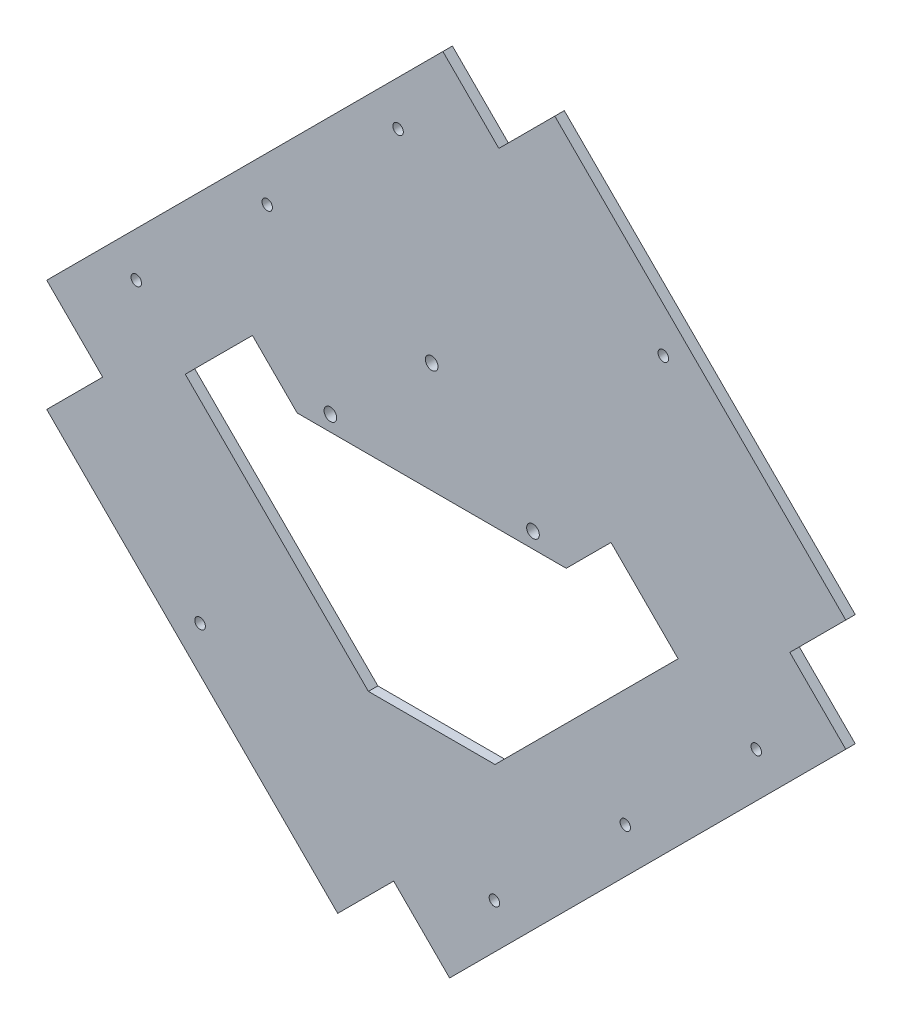
SolidWorks part; units mm, degrees
material "Thornel Mat VMA"
ref_plane "前视基准面" through (0, 0, 0) normal (0, 0, 1) x (1, 0, 0)
ref_plane "上视基准面" through (0, 0, 0) normal (0, 1, 0) x (1, 0, 0)
ref_plane "右视基准面" through (0, 0, 0) normal (1, 0, 0) x (0, 0, -1)
sketch "草图1" plane through (0, 0, 0) normal (0, 0, 1) x (1, 0, 0)
  line L0 (-20, 0) -> (20, 0)
  line L1 (0, 211.4264) -> (0, -109.6) construction
  line L2 (20, 0) -> (77.8553, 57.8553)
  line L3 (77.8553, 57.8553) -> (56.6421, 79.0685)
  line L4 (56.6421, 79.0685) -> (42.5, 64.9264)
  line L5 (42.5, 64.9264) -> (-42.5, 64.9264)
  line L6 (-42.5, 64.9264) -> (-56.6421, 79.0685)
  line L7 (-56.6421, 79.0685) -> (-77.8553, 57.8553)
  line L8 (-77.8553, 57.8553) -> (-20, 0)
  line L10 (-77.8553, 101.8264) -> (77.8553, 101.8264) construction
  line L11 (-77.8553, 101.8264) -> (-77.8553, 0) construction
  line L12 (-77.8553, 0) -> (77.8553, 0) construction
  line L13 (77.8553, 101.8264) -> (77.8553, 0) construction
  line L14 (-77.8553, 101.8264) -> (77.8553, 0) construction
  line L15 (-77.8553, 0) -> (77.8553, 101.8264) construction
  line L19 (0, 50.9132) -> (160.5132, 50.9132) construction
  line L26 (0, 50.9132) -> (-160.5132, 50.9132) construction
  line L27 (-160.5132, 50.9132) -> (0, 211.4264)
  line L28 (0, 211.4264) -> (160.5132, 50.9132)
  line L29 (160.5132, 50.9132) -> (0, -109.6)
  line L30 (0, -109.6) -> (-160.5132, 50.9132)
  circle A0 centre (-32, 69.8264) radius 2
  circle A1 centre (32, 69.8264) radius 2
  circle A2 centre (0, 99.8264) radius 2
  point P13 (0, 50.9132)
  point P18 (0, 50.9132)
  dimension "D5" = 4.9
  dimension "D6" = 4
  dimension "D7" = 34.9
  dimension "D8" = 64
  dimension "D1" = 85
  dimension "D2" = 40
  dimension "D3" = 30
  dimension "D4" = 20
  dimension "D9" = 227
extrude "凸台-拉伸1" add sketch "草图1" along normal blind 3
sketch "草图3" plane through (0, 0, 0) normal (0, 0, -1) x (-1, 0, 0)
  line L0 (-146.2, 65.2264) -> (27, 65.2264) construction
  line L1 (-146.2, 65.2264) -> (27, 65.2264)
  line L2 (0, 103.8264) -> (0, -109.6) construction
  line L3 (0, 103.8264) -> (0, -109.6)
sketch "草图4" plane through (0, 0, 3) normal (0, 0, 1) x (1, 0, 0)
  line L4 (-160.5132, 65.2264) -> (-160.5132, 50.9132)
  line L5 (0, -95.2868) -> (160.5132, 65.2264)
  line L6 (160.5132, 65.2264) -> (0, 225.7396) construction
  line L7 (0, 225.7396) -> (-160.5132, 65.2264) construction
  line L8 (0, 103.8264) -> (0, -109.6) construction
  line L9 (160.5132, 65.2264) -> (160.5132, 50.9132)
  line L16 (-160.5132, 65.2264) -> (0, -95.2868)
  line L17 (146.2, 65.2264) -> (-27, 65.2264) construction
  line L18 (160.5132, 50.9132) -> (0, 211.4264)
  line L19 (0, 211.4264) -> (-160.5132, 50.9132)
  line L20 (-160.5132, 50.9132) -> (0, -109.6)
  line L21 (0, -109.6) -> (160.5132, 50.9132)
  line L22 (160.5132, 50.9132) -> (0, 211.4264) construction
  line L23 (0, 211.4264) -> (-160.5132, 50.9132) construction
  line L24 (-160.5132, 50.9132) -> (0, -109.6)
  line L25 (0, -109.6) -> (160.5132, 50.9132)
  dimension "D2" = 0
  dimension "D1" = 227
extrude "切除-拉伸2" cut sketch "草图4" against normal blind 10
sketch "草图5" plane through (0, 0, 3) normal (0, 0, 1) x (1, 0, 0)
  line L0 (0, 225.7396) -> (-160.5132, 65.2264) construction
  line L1 (0, 225.7396) -> (-160.5132, 65.2264)
  line L2 (160.5132, 65.2264) -> (0, 225.7396) construction
  line L3 (160.5132, 65.2264) -> (0, 225.7396)
  line L4 (0, 211.4264) -> (-160.5132, 50.9132) construction
  line L5 (0, 211.4264) -> (-153.3566, 58.0698)
  line L6 (160.5132, 50.9132) -> (0, 211.4264) construction
  line L7 (153.3566, 58.0698) -> (0, 211.4264)
  line L8 (-160.5132, 65.2264) -> (-153.3566, 58.0698)
  line L9 (153.3566, 58.0698) -> (160.5132, 65.2264)
extrude "凸台-拉伸2" add sketch "草图5" against normal up to surface (3 mm away) up to face at (0, 58.0698, 0)
sketch "草图6" plane through (0, 0, 3) normal (0, 0, 1) x (1, 0, 0)
  line L0 (160.5132, 65.2264) -> (0, 225.7396) construction
  line L1 (0, 211.5975) -> (-146.3711, 65.2264) construction
  line L2 (-146.3711, 65.2264) -> (0, -81.1447) construction
  line L3 (0, -81.1447) -> (146.3711, 65.2264) construction
  line L4 (146.3711, 65.2264) -> (0, 211.5975) construction
  line L5 (0, 225.7396) -> (-160.5132, 65.2264) construction
  line L6 (0, -95.2868) -> (-160.5132, 65.2264) construction
  line L7 (-65.7609, 145.8366) -> (80.6102, -0.5345) construction
  line L8 (73.1007, 152.6389) -> (-87.4125, -7.8743) construction
  line L9 (160.5132, 65.2264) -> (0, 225.7396) construction
  line L10 (-160.5132, 65.2264) -> (0, -95.2868) construction
  line L11 (0, 225.7396) -> (-160.5132, 65.2264) construction
  circle A0 centre (0, 65.2264) radius 103.5 construction
  circle A1 centre (0, 211.5975) radius 1.675
  circle A2 centre (73.1856, 138.412) radius 1.675
  circle A3 centre (146.3711, 65.2264) radius 1.675
  circle A4 centre (73.1856, -7.9591) radius 1.675
  circle A5 centre (0, -81.1447) radius 1.675
  circle A6 centre (-73.1856, -7.9591) radius 1.675
  circle A7 centre (-146.3711, 65.2264) radius 1.675
  circle A8 centre (-73.1856, 138.412) radius 1.675 construction
  circle A9 centre (-45.9619, 165.6356) radius 1.625
  circle A10 centre (-30.4056, 110.4812) radius 1.625 construction
  circle A11 centre (34.2098, 113.7481) radius 1.675 construction
  dimension "D4" = 3.35
  dimension "D5" = 3.25
  dimension "D8" = 3.25
  dimension "D9" = 50
  dimension "D1" = 10
  dimension "D2" = 10
  dimension "D3" = 10
  dimension "D6" = 65
  dimension "D7" = 93
  dimension "D10" = 103.38
  dimension "D11" = 45
extrude "切除-拉伸3" cut sketch "草图6" against normal blind 85
sketch "草图7" plane through (0, 0, 0) normal (0, 0, -1) x (-1, 0, 0)
  line L0 (0, 225.7396) -> (160.5132, 65.2264)
  line L1 (160.5132, 65.2264) -> (139.3, 44.0132)
  line L2 (160.5132, 65.2264) -> (0, -95.2868) construction
  line L3 (139.3, 44.0132) -> (-21.2132, 204.5264)
  line L4 (-160.5132, 65.2264) -> (0, 225.7396) construction
  line L5 (-21.2132, 204.5264) -> (0, 225.7396)
  line L6 (-148.4924, 77.2472) -> (12.0208, -83.266)
  line L7 (12.0208, -83.266) -> (0, -95.2868)
  line L8 (0, -95.2868) -> (-160.5132, 65.2264)
  line L9 (-160.5132, 65.2264) -> (-148.4924, 77.2472)
  line L10 (-38.8909, 186.8488) -> (-21.2132, 169.1711)
  line L11 (-21.2132, 169.1711) -> (-3.5355, 186.8488)
  line L12 (80.2566, 145.483) -> (-68.2358, -3.0094) construction
  line L13 (-38.8909, 186.8488) -> (-21.2132, 204.5264)
  line L14 (-148.4924, 77.2472) -> (-130.8148, 94.9249)
  line L15 (-130.8148, 94.9249) -> (-113.1371, 77.2472)
  line L16 (-113.1371, 77.2472) -> (-130.8148, 59.5696)
  line L17 (12.0208, -47.9107) -> (-5.6569, -65.5883)
  line L18 (29.6985, -65.5883) -> (12.0208, -47.9107)
  line L19 (12.0208, -83.266) -> (29.6985, -65.5883)
  line L20 (121.6224, 26.3355) -> (139.3, 44.0132)
  line L21 (103.9447, 44.0132) -> (121.6224, 61.6909)
  line L22 (121.6224, 26.3355) -> (103.9447, 44.0132)
  circle M4 centre (0, 211.5975) radius 1.675
  circle M7 centre (45.9619, 165.6356) radius 1.625
  circle M8 centre (146.3711, 65.2264) radius 1.675
  circle M10 centre (0, -81.1447) radius 1.675
  circle M11 centre (-73.1856, -7.9591) radius 1.675
  circle M12 centre (-146.3711, 65.2264) radius 1.675
  line M14 (0, -95.2868) -> (160.5132, 65.2264)
  line M15 (160.5132, 65.2264) -> (0, 225.7396)
  line M16 (0, 225.7396) -> (-160.5132, 65.2264)
  line M17 (-160.5132, 65.2264) -> (0, -95.2868)
  dimension "D1" = 30
  dimension "D2" = 180
  dimension "D3" = 25
extrude "切除-拉伸4" cut sketch "草图7" against normal through all contours L10 L11 L3 M16 | L22 L3 L21 M14 | L12 L3 M15 M14 M8 | L12 L0 L3 M16 M7 M4 | L16 L15 L6 M16 | L6 M16 M17 M14 M10 M12 M11 | L18 L17 L6 M14
sketch "草图8" plane through (0, 0, 0) normal (0, 0, -1) x (-1, 0, 0)
  line L0 (-10.6066, 179.7777) -> (114.5513, 54.6198) construction
  line L1 (-21.2132, 169.1711) -> (-3.5355, 186.8488) construction
  line L2 (103.9447, 44.0132) -> (121.6224, 61.6909) construction
  line L3 (1.4142, -58.5173) -> (-123.7437, 66.6406) construction
  line L4 (12.0208, -47.9107) -> (-5.6569, -65.5883) construction
  line L5 (-113.1371, 77.2472) -> (-130.8148, 59.5696) construction
  line L6 (-130.8148, 59.5696) -> (-5.6569, -65.5883) construction
  line L7 (121.6224, 61.6909) -> (-3.5355, 186.8488) construction
  circle A0 centre (10.6066, 158.5645) radius 1.65
  circle A1 centre (51.9723, 117.1988) radius 1.65
  circle A2 centre (93.3381, 75.833) radius 1.65
  circle A3 centre (-102.5305, 45.4274) radius 1.65
  circle A4 centre (-61.1647, 4.0617) radius 1.65
  circle A5 centre (-19.799, -37.3041) radius 1.65
  dimension "D3" = 3.3
  dimension "D4" = 30
  dimension "D1" = 10
  dimension "D2" = 10
  dimension "D5" = 30
  dimension "D6" = 30
  dimension "D7" = 30
extrude "切除-拉伸5" cut sketch "草图8" against normal blind 10
